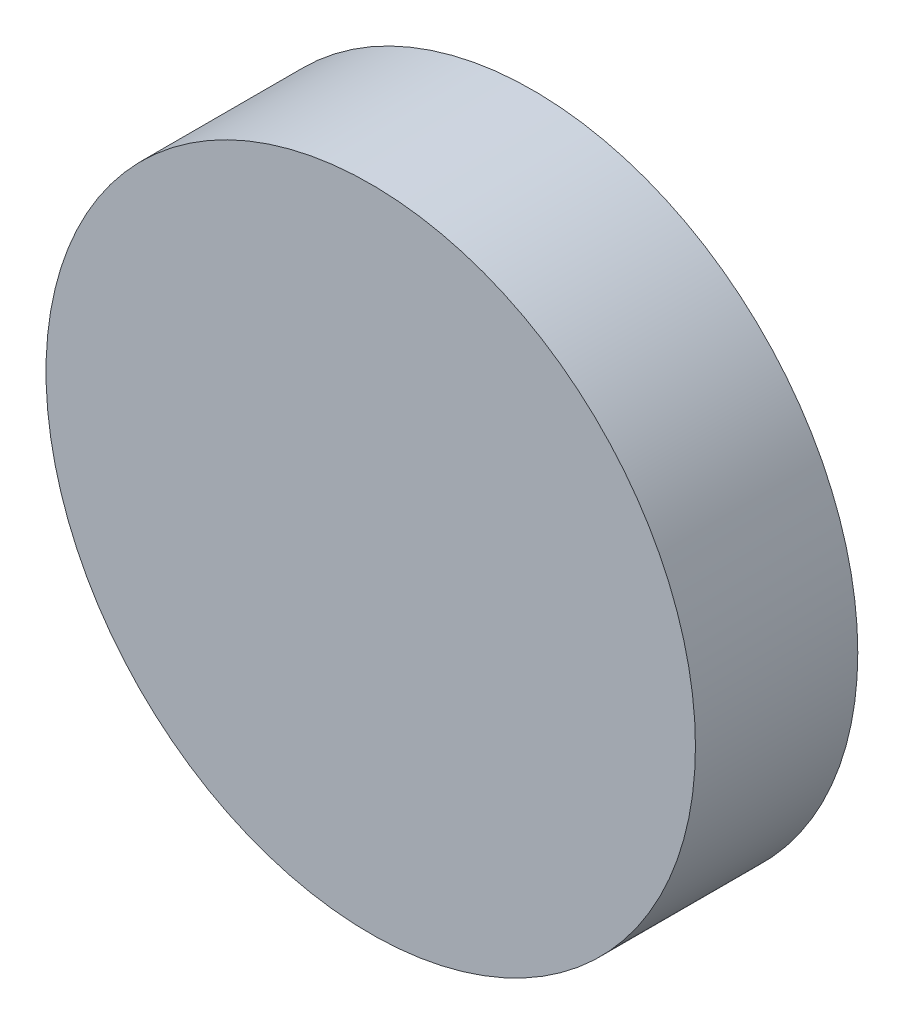
SolidWorks part; units mm, degrees
ref_plane "Plano frontal" through (0, 0, 0) normal (0, 0, 1) x (1, 0, 0)
ref_plane "Plano superior" through (0, 0, 0) normal (0, 1, 0) x (1, 0, 0)
ref_plane "Plano direito" through (0, 0, 0) normal (1, 0, 0) x (0, 0, -1)
sketch "Esboço1" plane through (0, 0, 0) normal (0, 0, 1) x (1, 0, 0)
  circle A0 centre (0, 0) radius 4
extrude "Ressalto-extrusão1" add sketch "Esboço1" along normal blind 2
